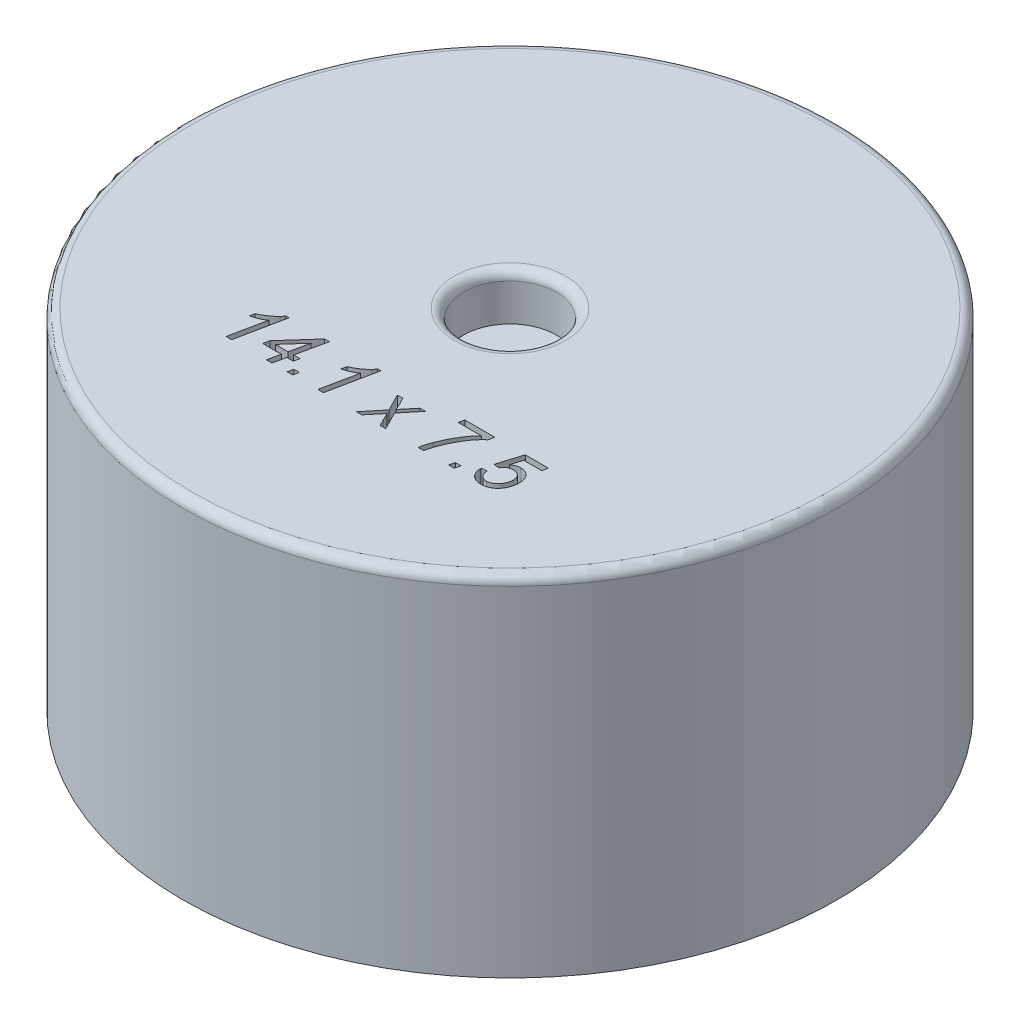
SolidWorks part; units mm, degrees
ref_plane "Спереди" through (0, 0, 0) normal (0, 0, 1) x (1, 0, 0)
ref_plane "Сверху" through (0, 0, 0) normal (0, 1, 0) x (1, 0, 0)
ref_plane "Справа" through (0, 0, 0) normal (1, 0, 0) x (0, 0, -1)
sketch "Эскиз1" plane through (0, 0, 0) normal (0, 1, 0) x (1, 0, 0)
  circle A0 centre (0, 0) radius 7.05
  dimension "D1" = 14.1
extrude "Бобышка-Вытянуть1" add sketch "Эскиз1" along normal blind 7.5
fillet "Скругление1" radius 0.2 1 edges at (0, 7.5, 7.05)
sketch "Эскиз2" plane through (0, 7.5, 0) normal (0, 1, 0) x (1, 0, 0)
  circle A0 centre (0, 0) radius 1
  dimension "D1" = 2
extrude "Вырез-Вытянуть1" cut sketch "Эскиз2" against normal blind 1
fillet "Скругление2" radius 0.2 1 edges at (0, 7.5, 1)
sketch "Эскиз3" plane through (0, 0, 0) normal (0, -1, 0) x (1, 0, 0)
  circle A0 centre (-3.81, 0) radius 0.35
  circle A1 centre (3.81, 0) radius 0.35
  dimension "D1" = 0.7
  dimension "D2" = 3.81
  dimension "D3" = 2
extrude "Бобышка-Вытянуть2" add sketch "Эскиз3" along normal blind 2
sketch "Эскиз4" plane through (0, 7.5, 0) normal (0, 1, 0) x (1, 0, 0)
  text T0 "14.1 x 7.5" font "Arial" height in points 4
extrude "Вырез-Вытянуть2" cut sketch "Эскиз4" against normal blind 0.5
